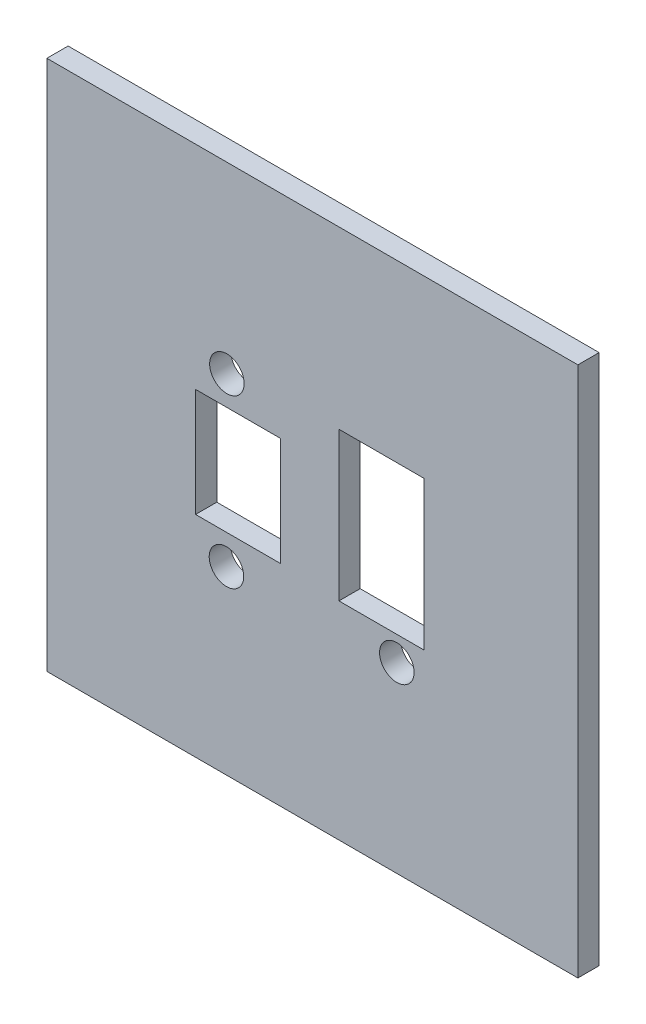
SolidWorks part; units mm, degrees
ref_plane "Front Plane" through (0, 0, 0) normal (0, 0, 1) x (1, 0, 0)
ref_plane "Top Plane" through (0, 0, 0) normal (0, 1, 0) x (1, 0, 0)
ref_plane "Right Plane" through (0, 0, 0) normal (1, 0, 0) x (0, 0, -1)
sketch "Sketch1" plane through (0, 0, 0) normal (0, 0, 1) x (1, 0, 0)
  line L1 (0, 0) -> (50, 0)
  line L2 (0, 0) -> (0, 50)
  line L3 (0, 50) -> (50, 50)
  line L4 (50, 0) -> (50, 50)
  dimension "D1" = 50
  dimension "D2" = 50
extrude "Boss-Extrude1" add sketch "Sketch1" along normal blind 2
sketch "Sketch2" plane through (0, 0, 2) normal (0, 0, 1) x (1, 0, 0)
  circle A0 centre (16.95, 32.75) radius 1.625
  circle A1 centre (16.91, 17) radius 1.625
  circle A2 centre (32.95, 17.2) radius 1.625
  dimension "D1" = 3.25
  dimension "D2" = 3.25
  dimension "D3" = 3.25
extrude "Cut-Extrude1" cut sketch "Sketch2" against normal up to next
sketch "Sketch3" plane through (0, 0, 2) normal (0, 0, 1) x (1, 0, 0)
  line L0 (50, 0) -> (50, 50) construction
  line L1 (14, 30) -> (22, 30)
  line L2 (14, 30) -> (14, 19.8)
  line L3 (14, 19.8) -> (22, 19.8)
  line L4 (22, 30) -> (22, 19.8)
  line L5 (27.5, 33.5) -> (35.5, 33.5)
  line L6 (27.5, 33.5) -> (27.5, 19.5)
  line L7 (27.5, 19.5) -> (35.5, 19.5)
  line L8 (35.5, 33.5) -> (35.5, 19.5)
  line L9 (50, 50) -> (0, 50) construction
  line L11 (0, 50) -> (0, 0) construction
  dimension "D1" = 8
  dimension "D2" = 8
  dimension "D3" = 14.5
  dimension "D4" = 14
  dimension "D5" = 16.5
  dimension "D6" = 10.2
  dimension "D7" = 20
  dimension "D8" = 14
extrude "Cut-Extrude2" cut sketch "Sketch3" against normal up to next
